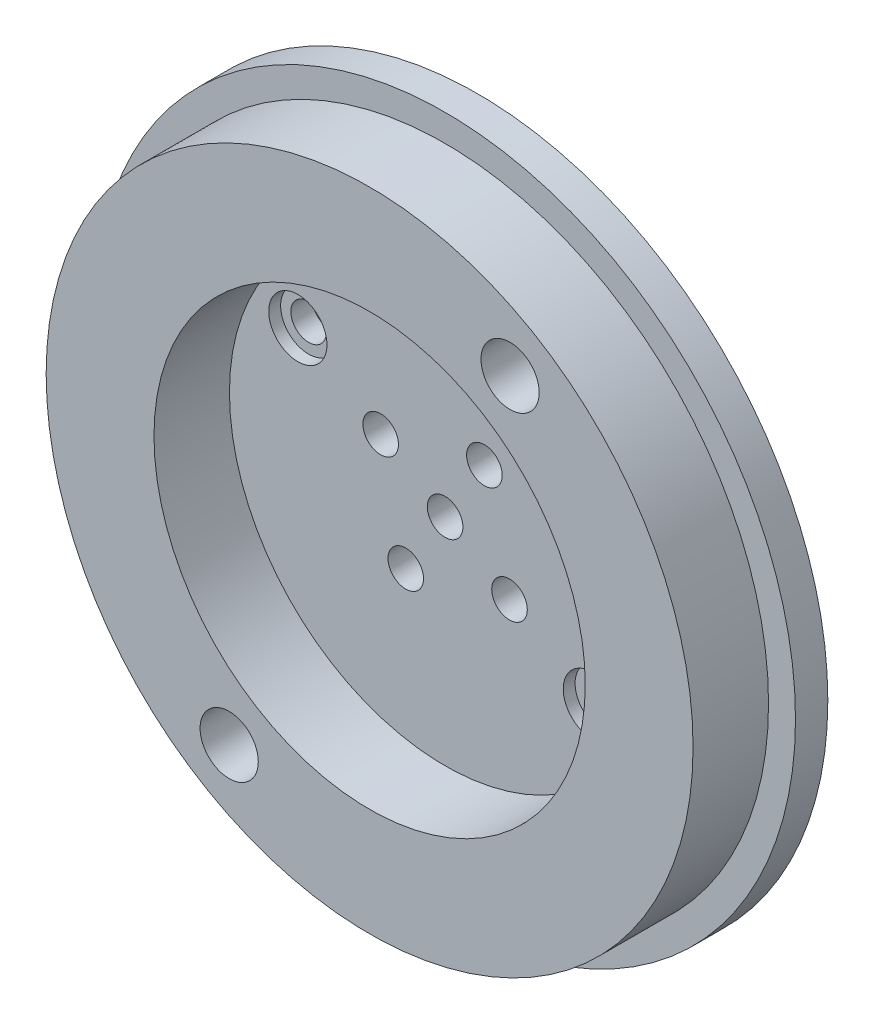
SolidWorks part; units mm, degrees
ref_plane "前视基准面" through (0, 0, 0) normal (0, 0, 1) x (1, 0, 0)
ref_plane "上视基准面" through (0, 0, 0) normal (0, 1, 0) x (1, 0, 0)
ref_plane "右视基准面" through (0, 0, 0) normal (1, 0, 0) x (0, 0, -1)
other "Configuration Table"
sketch "草图1" plane through (0, 0, 0) normal (0, 0, 1) x (1, 0, 0)
  circle A0 centre (0, 0) radius 32.5
  dimension "D1" = 65
extrude "凸台-拉伸1" add sketch "草图1" along normal blind 3
sketch "草图2" plane through (0, 0, 3) normal (0, 0, 1) x (1, 0, 0)
  circle A0 centre (0, 0) radius 30
  dimension "D1" = 60
extrude "凸台-拉伸2" add sketch "草图2" along normal blind 7
sketch "草图3" plane through (0, 0, 10) normal (0, 0, 1) x (1, 0, 0)
  circle A0 centre (0, 0) radius 20
  dimension "D1" = 40
extrude "切除-拉伸2" cut sketch "草图3" against normal blind 7
sketch "草图4" plane through (0, 0, 10) normal (0, 0, 1) x (1, 0, 0)
  circle A0 centre (-13.0256, -21.3362) radius 2.7
  circle A1 centre (13.0256, 21.3362) radius 2.7
  circle A2 centre (13.6563, -8.3371) radius 2.7
  circle A3 centre (-13.6563, 8.3371) radius 2.7
  dimension "D1" = 5.4
  dimension "D2" = 5.4
  dimension "D3" = 5.4
  dimension "D4" = 5.4
extrude "切除-拉伸3" cut sketch "草图4" against normal blind 10
sketch "草图5" plane through (0, 0, 0) normal (0, 0, -1) x (-1, 0, 0)
  circle A0 centre (13.0256, -21.3362) radius 2.6
  circle A1 centre (13.0256, -21.3362) radius 1.65
  circle A2 centre (-13.0256, 21.3362) radius 2.6
  circle A3 centre (-13.0256, 21.3362) radius 1.65
  circle A4 centre (-13.6563, -8.3371) radius 2.6
  circle A5 centre (-13.6563, -8.3371) radius 1.65
  circle A6 centre (13.6563, 8.3371) radius 2.6
  circle A7 centre (13.6563, 8.3371) radius 1.65
  dimension "D1" = 3.3
  dimension "D2" = 3.3
  dimension "D3" = 3.3
  dimension "D4" = 3.3
extrude "凸台-拉伸3" add sketch "草图5" against normal blind 2
sketch "草图6" plane through (0, 0, 0) normal (0, 0, -1) x (-1, 0, 0)
  line L0 (13.6563, 8.3371) -> (-13.6563, -8.3371) construction
  circle A0 centre (0, 0) radius 1.65
  circle A1 centre (0, 0) radius 7 construction
  circle A2 centre (5.9746, 3.6475) radius 1.65
  circle A3 centre (3.6475, -5.9746) radius 1.65
  circle A4 centre (0, 0) radius 7 construction
  circle A5 centre (-5.9746, -3.6475) radius 1.65
  circle A6 centre (0, 0) radius 7 construction
  circle A7 centre (-3.6475, 5.9746) radius 1.65
  circle A8 centre (0, 0) radius 7 construction
  point P22 (0, 0)
  dimension "D1" = 3.3
  dimension "D2" = 14
  dimension "D3" = 3.3
  dimension "D4" = 4
extrude "切除-拉伸4" cut sketch "草图6" against normal blind 10
